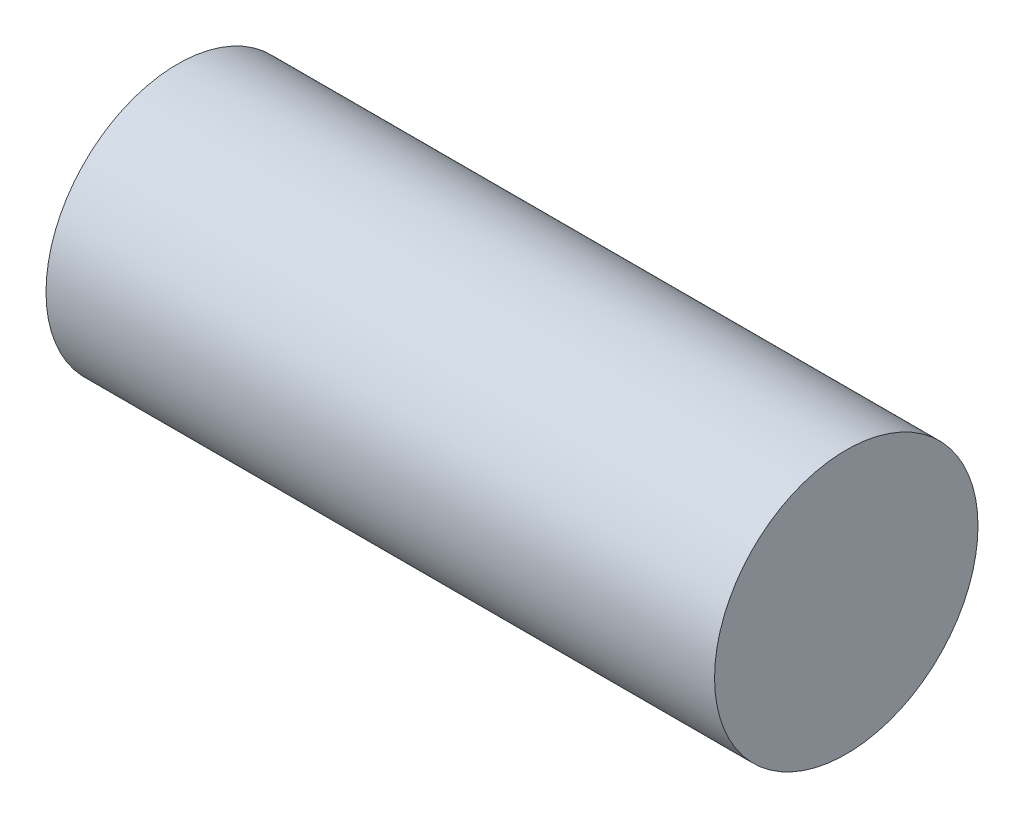
SolidWorks part; units mm, degrees
ref_plane "Front Plane" through (0, 0, 0) normal (0, 0, 1) x (1, 0, 0)
ref_plane "Top Plane" through (0, 0, 0) normal (0, 1, 0) x (1, 0, 0)
ref_plane "Right Plane" through (0, 0, 0) normal (1, 0, 0) x (0, 0, -1)
sketch "Sketch1" plane through (0, 0, 0) normal (1, 0, 0) x (0, 0, -1)
  circle A0 centre (364.1509, 35.1472) radius 10.3228
  point P2 (353.8281, 35.1472)
extrude "Boss-Extrude1" add sketch "Sketch1" against normal blind 52.3951
